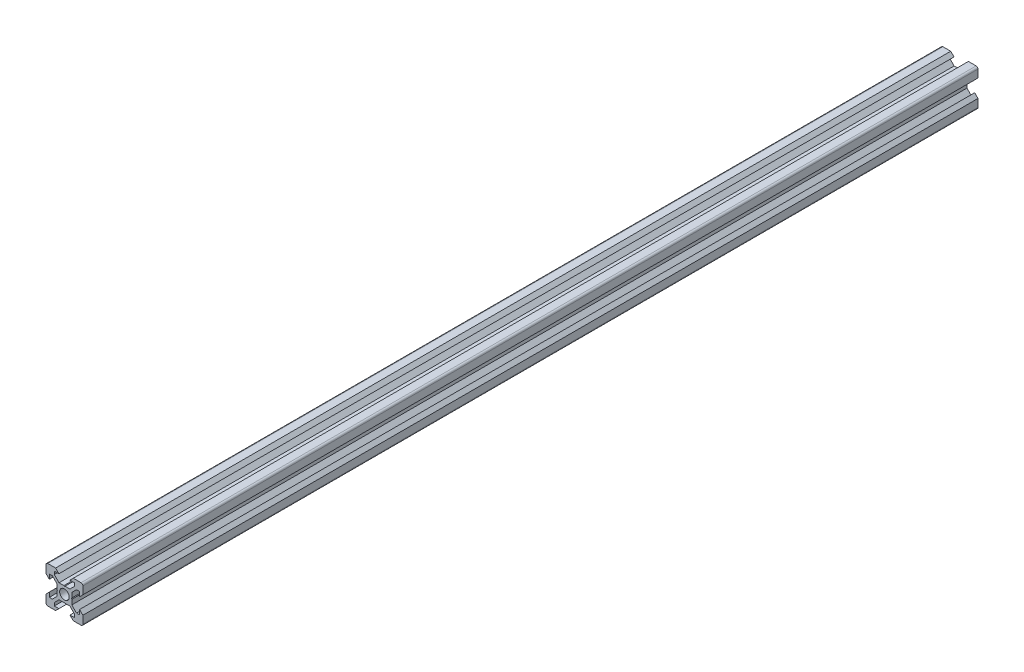
SolidWorks part; units mm, degrees
material "1060-H12 Rod (SS)"
ref_plane "Front Plane" through (0, 0, 0) normal (0, 0, 1) x (1, 0, 0)
ref_plane "Top Plane" through (0, 0, 0) normal (0, 1, 0) x (1, 0, 0)
ref_plane "Right Plane" through (0, 0, 0) normal (1, 0, 0) x (0, 0, -1)
sketch "Sketch1" plane through (0, 0, 0) normal (0, 0, 1) x (1, 0, 0)
  line B0 (10.3368, -8.1134) -> (10.3368, -3.9134)
  line B1 (10.3368, -3.9134) -> (8.5368, -2.1134)
  line B2 (8.5368, -2.1134) -> (8.5368, -4.6134)
  line B3 (8.5368, -4.6134) -> (6.8974, -4.6134)
  line B4 (6.8974, -4.6134) -> (4.3368, -2.0527)
  line B5 (4.3368, -2.0527) -> (4.3368, 0.5866)
  line B6 (4.3368, 0.5866) -> (4.0368, 0.8866)
  line B7 (4.0368, 0.8866) -> (4.3368, 1.1866)
  line B8 (4.3368, 1.1866) -> (4.3368, 3.826)
  line B9 (4.3368, 3.826) -> (6.8974, 6.3866)
  line B10 (6.8974, 6.3866) -> (8.5368, 6.3866)
  line B11 (8.5368, 6.3866) -> (8.5368, 3.8866)
  line B12 (8.5368, 3.8866) -> (10.3368, 5.6866)
  line B13 (10.3368, 5.6866) -> (10.3368, 9.8866)
  line B14 (9.3368, 10.8866) -> (5.1368, 10.8866)
  line B15 (5.1368, 10.8866) -> (3.3368, 9.0866)
  line B16 (3.3368, 9.0866) -> (5.8368, 9.0866)
  line B17 (5.8368, 9.0866) -> (5.8368, 7.4473)
  line B18 (5.8368, 7.4473) -> (3.2761, 4.8866)
  line B19 (3.2761, 4.8866) -> (0.6368, 4.8866)
  line B20 (0.6368, 4.8866) -> (0.3368, 4.5866)
  line B21 (0.3368, 4.5866) -> (0.0368, 4.8866)
  line B22 (0.0368, 4.8866) -> (-2.6026, 4.8866)
  line B23 (-2.6026, 4.8866) -> (-5.1632, 7.4473)
  line B24 (-5.1632, 7.4473) -> (-5.1632, 9.0866)
  line B25 (-5.1632, 9.0866) -> (-2.6632, 9.0866)
  line B26 (-2.6632, 9.0866) -> (-4.4632, 10.8866)
  line B27 (-4.4632, 10.8866) -> (-8.6632, 10.8866)
  line B28 (-9.6632, 9.8866) -> (-9.6632, 5.6866)
  line B29 (-9.6632, 5.6866) -> (-7.8632, 3.8866)
  line B30 (-7.8632, 3.8866) -> (-7.8632, 6.3866)
  line B31 (-7.8632, 6.3866) -> (-6.2239, 6.3866)
  line B32 (-6.2239, 6.3866) -> (-3.6632, 3.826)
  line B33 (-3.6632, 3.826) -> (-3.6632, 1.1866)
  line B34 (-3.6632, 1.1866) -> (-3.3632, 0.8866)
  line B35 (-3.3632, 0.8866) -> (-3.6632, 0.5866)
  line B36 (-3.6632, 0.5866) -> (-3.6632, -2.0527)
  line B37 (-3.6632, -2.0527) -> (-6.2239, -4.6134)
  line B38 (-6.2239, -4.6134) -> (-7.8632, -4.6134)
  line B39 (-7.8632, -4.6134) -> (-7.8632, -2.1134)
  line B40 (-7.8632, -2.1134) -> (-9.6632, -3.9134)
  line B41 (-9.6632, -3.9134) -> (-9.6632, -8.1134)
  line B42 (-8.6632, -9.1134) -> (-4.4632, -9.1134)
  line B43 (-4.4632, -9.1134) -> (-2.6632, -7.3134)
  line B44 (-2.6632, -7.3134) -> (-5.1632, -7.3134)
  line B45 (-5.1632, -7.3134) -> (-5.1632, -5.674)
  line B46 (-5.1632, -5.674) -> (-2.6026, -3.1134)
  line B47 (-2.6026, -3.1134) -> (0.0368, -3.1134)
  line B48 (0.0368, -3.1134) -> (0.3368, -2.8134)
  line B49 (0.3368, -2.8134) -> (0.6368, -3.1134)
  line B50 (0.6368, -3.1134) -> (3.2761, -3.1134)
  line B51 (3.2761, -3.1134) -> (5.8368, -5.674)
  line B52 (5.8368, -5.674) -> (5.8368, -7.3134)
  line B53 (5.8368, -7.3134) -> (3.3368, -7.3134)
  line B54 (3.3368, -7.3134) -> (5.1368, -9.1134)
  line B55 (5.1368, -9.1134) -> (9.3368, -9.1134)
  arc B56 (9.3368, -9.1134) -> (10.3368, -8.1134) centre (9.3368, -8.1134) ccw
  arc B57 (10.3368, 9.8866) -> (9.3368, 10.8866) centre (9.3368, 9.8866) ccw
  arc B58 (-8.6632, 10.8866) -> (-9.6632, 9.8866) centre (-8.6632, 9.8866) ccw
  arc B59 (-9.6632, -8.1134) -> (-8.6632, -9.1134) centre (-8.6632, -8.1134) ccw
  circle B60 centre (0.3368, 0.8866) radius 2.6
sketch_block_instance "AL profile  block  -1"
sketch_block "AL profile  block  " parameters "D1"=4.1771
extrude "Boss-Extrude1" add sketch "Sketch1" along normal up to surface (485.7 mm away)
